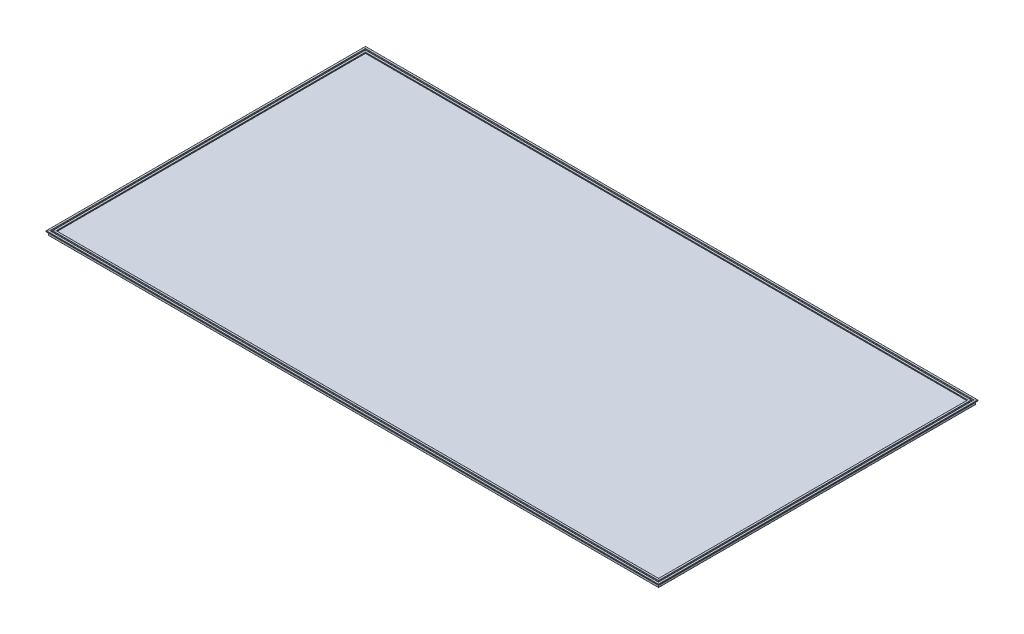
SolidWorks part; units mm, degrees
ref_plane "Front Plane" through (0, 0, 0) normal (0, 0, 1) x (1, 0, 0)
ref_plane "Top Plane" through (0, 0, 0) normal (0, 1, 0) x (1, 0, 0)
ref_plane "Right Plane" through (0, 0, 0) normal (1, 0, 0) x (0, 0, -1)
sketch "Sketch1" plane through (0, 0, 0) normal (0, 1, 0) x (1, 0, 0)
  line L1 (0, 0) -> (288, 0)
  line L2 (0, 0) -> (0, -149)
  line L3 (0, -149) -> (288, -149)
  line L4 (288, 0) -> (288, -149)
  dimension "D1" = 288
  dimension "D2" = 149
ref_plane "Plane1" through (144, 0, 0) normal (1, 0, 0) x (0, 0, -1)
sketch "Sketch2" plane through (144, 0, 0) normal (1, 0, 0) x (0, 0, -1)
  line L1 (0, 0) -> (-149, 0) construction
  line L3 (-147.85, 2) -> (-148.65, 2)
  line L4 (-148.75, 1.9) -> (-148.75, 0.6)
  line L5 (-148.85, 0.5) -> (-149.15, 0.5)
  line L6 (-149.25, 0.6) -> (-149.25, 1.9)
  line L7 (-149.35, 2) -> (-150.15, 2)
  line L10 (-149.55, 0) -> (-148.45, 0)
  line L11 (-149.65, 0.1) -> (-149.65, 1.4)
  line L12 (-149.75, 1.5) -> (-150.15, 1.5)
  line L13 (-150.25, 1.6) -> (-150.25, 1.9)
  line L14 (-148.35, 0.1) -> (-148.35, 1.4)
  line L15 (-148.25, 1.5) -> (-147.85, 1.5)
  line L16 (-147.75, 1.6) -> (-147.75, 1.9)
  arc A0 (-149.15, 0.5) -> (-149.25, 0.6) centre (-149.15, 0.6) cw
  arc A1 (-148.85, 0.5) -> (-148.75, 0.6) centre (-148.85, 0.6) ccw
  arc A2 (-148.75, 1.9) -> (-148.65, 2) centre (-148.65, 1.9) cw
  arc A3 (-147.85, 2) -> (-147.75, 1.9) centre (-147.85, 1.9) cw
  arc A4 (-147.75, 1.6) -> (-147.85, 1.5) centre (-147.85, 1.6) cw
  arc A5 (-148.25, 1.5) -> (-148.35, 1.4) centre (-148.25, 1.4) ccw
  arc A6 (-148.35, 0.1) -> (-148.45, 0) centre (-148.45, 0.1) cw
  arc A7 (-149.55, 0) -> (-149.65, 0.1) centre (-149.55, 0.1) cw
  arc A8 (-149.65, 1.4) -> (-149.75, 1.5) centre (-149.75, 1.4) ccw
  arc A9 (-149.25, 1.9) -> (-149.35, 2) centre (-149.35, 1.9) ccw
  arc A10 (-150.15, 1.5) -> (-150.25, 1.6) centre (-150.15, 1.6) cw
  arc A11 (-150.25, 1.9) -> (-150.15, 2) centre (-150.15, 1.9) cw
  point P1 (-149, 0)
  point P18 (-149.25, 0.5)
  point P21 (-148.75, 0.5)
  point P24 (-148.75, 2)
  point P33 (-148.35, 0)
  point P40 (-149.25, 2)
  point P45 (0, 0)
  dimension "D3" = 0.1
  dimension "D1" = 2.5
  dimension "D2" = 0.5
  dimension "D4" = 1.5
  dimension "D5" = 2
  dimension "D6" = 0.5
  dimension "D7" = 0.4
sweep "Sweep1" add profiles "Sketch2" path "Sketch1"
surface "Surface-Fill1"
